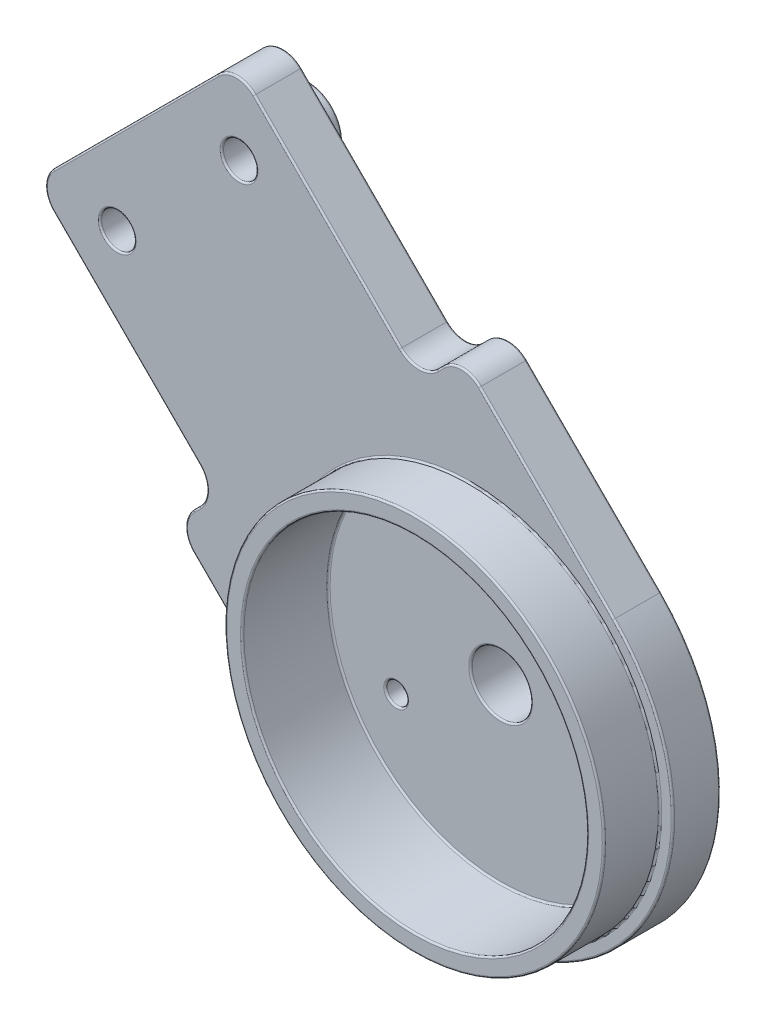
SolidWorks part; units mm, degrees
ref_plane "Front Plane" through (0, 0, 0) normal (0, 0, 1) x (1, 0, 0)
ref_plane "Top Plane" through (0, 0, 0) normal (0, 1, 0) x (1, 0, 0)
ref_plane "Right Plane" through (0, 0, 0) normal (1, 0, 0) x (0, 0, -1)
sketch "Sketch1" plane through (0, 0, 0) normal (0, 0, 1) x (1, 0, 0)
  line L0 (-100, 0) -> (100, 0) construction
  line L1 (-100, 0) -> (0, 100) construction
  line L2 (0, 100) -> (100, 0) construction
  line L3 (0, 0) -> (-50, 50) construction
  line L4 (-50, 50) -> (0, 0) construction
  line L5 (-40, 60) -> (40, 60) construction
  line L6 (0, 100) -> (0, 60) construction
  circle A0 centre (-100, 0) radius 20
  circle A1 centre (0, 0) radius 20
  circle A2 centre (100, 0) radius 20
  point P5 (0, 0)
  dimension "D5" = 40
  dimension "D1" = 200
  dimension "D2" = 90
  dimension "D3" = 90
  dimension "D4" = 80
sketch "Sketch2" plane through (0, 0, 0) normal (0, 0, 1) x (1, 0, 0)
  line L0 (-56.5165, 43.4835) -> (-40, 60) construction
  line L1 (-100, 0) -> (0, 100) construction
  line L2 (-40, 60) -> (40, 60) construction
  line L3 (40, 60) -> (86.565, 13.435) construction
  line L4 (0, 100) -> (100, 0) construction
  line L5 (-49.4454, 36.4124) -> (-35.8579, 50)
  line L6 (-35.8579, 50) -> (35.8579, 50)
  line L7 (35.8579, 50) -> (79.4939, 6.364)
  line L8 (-63.5876, 50.5546) -> (-44.1421, 70)
  line L9 (-44.1421, 70) -> (44.1421, 70)
  line L10 (44.1421, 70) -> (93.636, 20.5061)
  line L11 (-63.5876, 50.5546) -> (-49.4454, 36.4124)
  line L12 (93.636, 20.5061) -> (79.4939, 6.364)
  line L13 (81.9688, 8.8388) -> (95.4038, -4.5962)
  line L14 (91.1612, 18.0312) -> (104.5962, 4.5962)
  line L15 (75.9584, 9.8995) -> (90.1005, 24.0416) construction
  line L16 (0, 100) -> (0, 60) construction
  line L17 (-6, 70) -> (-3.4326, 85.5452)
  line L18 (6, 70) -> (3.4532, 85.4203)
  circle A0 centre (100, 0) radius 3.5
  circle A1 centre (100, 0) radius 10 construction
  arc A2 (95.4038, -4.5962) -> (104.5962, 4.5962) centre (100, 0) ccw
  circle A3 centre (100, 0) radius 0.5
  circle A4 centre (100, 0) radius 6.5 construction
  circle A5 centre (79.4939, 13.435) radius 1
  circle A6 centre (86.565, 20.5061) radius 1
  circle A7 centre (0, 60) radius 1.5
  circle A8 centre (0, 84.85) radius 1.5
  arc A9 (3.4532, 85.4203) -> (-3.4532, 85.4203) centre (0, 84.85) ccw
  circle A10 centre (0, 84.85) radius 3.5 construction
  circle A11 centre (-50, 50) radius 1.5
  dimension "D4" = 20
  dimension "D5" = 7
  dimension "D11" = 3
  dimension "D15" = 3
  dimension "D16" = 2
  dimension "D3" = 27.5
  dimension "D8" = 19
  dimension "D9" = 5
  dimension "D10" = 5
  dimension "5" = 5
  dimension "D12" = 14.85
  dimension "D7" = 6
  dimension "D14" = 6
  dimension "D1" = 10
  dimension "D2" = 10
  dimension "D6" = 3
  dimension "D13" = 2
sketch "Sketch3" plane through (0, 0, 0) normal (0, 0, 1) x (1, 0, 0)
  line L0 (-100, 0) -> (100, 0) construction
  line L1 (-86.6719, 13.3281) -> (-50, 50) construction
  line L2 (-24.0416, 9.8995) -> (-9.8995, 24.0416) construction
  line L3 (-50, 50) -> (-13.435, 13.435) construction
  line L4 (0, 0) -> (-50, 50) construction
  line L5 (-79.4939, 6.364) -> (-50, 35.8579)
  line L6 (-50, 35.8579) -> (-20.5061, 6.364)
  line L7 (-93.636, 20.5061) -> (-50, 64.1421)
  line L8 (-50, 64.1421) -> (-6.364, 20.5061)
  line L9 (-81.6799, 4.1779) -> (-50, 35.8579) construction
  line L10 (-95.8221, 18.3201) -> (-50, 64.1421) construction
  line L11 (-93.636, 20.5061) -> (-79.4939, 6.364)
  line L12 (-20.5061, 6.364) -> (-6.364, 20.5061)
  line L13 (-81.9688, 8.8388) -> (-95.4038, -4.5962)
  line L14 (-91.1612, 18.0312) -> (-104.5962, 4.5962)
  line L15 (-18.0312, 8.8388) -> (-4.5962, -4.5962)
  line L16 (-8.8388, 18.0312) -> (4.5962, 4.5962)
  line L17 (-88.751, 11.249) -> (-50, 50) construction
  line L18 (-90.1005, 24.0416) -> (-76.1469, 10.088) construction
  circle A0 centre (-100, 0) radius 10 construction
  circle A1 centre (-100, 0) radius 3.5
  circle A2 centre (0, 0) radius 10 construction
  circle A3 centre (0, 0) radius 3.5
  arc A4 (-4.5962, -4.5962) -> (4.5962, 4.5962) centre (0, 0) ccw
  arc A5 (-104.5962, 4.5962) -> (-95.4038, -4.5962) centre (-100, 0) ccw
  circle A6 centre (-86.565, 20.5061) radius 1
  circle A7 centre (0, 0) radius 6.5 construction
  circle A8 centre (-100, 0) radius 6.5 construction
  circle A9 centre (-79.4939, 13.435) radius 1
  circle A10 centre (-20.5061, 13.435) radius 1
  circle A11 centre (-13.435, 20.5061) radius 1
  circle A12 centre (-50, 50) radius 1.5 construction
  circle A13 centre (-50, 50) radius 1.5
  dimension "D1" = 20
  dimension "D2" = 7
  dimension "D9" = 2
  dimension "D7" = 19
  dimension "D8" = 19
  dimension "D10" = 5
  dimension "D11" = 5
  dimension "D12" = 5
  dimension "D13" = 5
  dimension "D14" = 5
  dimension "D15" = 5
  dimension "D3" = 3
  dimension "D4" = 3
  dimension "D5" = 10
  dimension "D6" = 10
sketch "Sketch4" plane through (0, 0, 0) normal (0, 0, 1) x (1, 0, 0)
  line L1 (57.5, 96.35) -> (57.5, 86.35)
  line L2 (57.5, 86.35) -> (44.1421, 70)
  line L3 (44.1421, 70) -> (-44.1421, 70)
  line L4 (-44.1421, 70) -> (-57.5, 86.35)
  line L5 (-57.5, 86.35) -> (-57.5, 96.35)
  line L7 (-57.5, 96.35) -> (57.5, 96.35)
  line L8 (-4, 60) -> (-4, 70)
  line L9 (4, 60) -> (4, 70)
  line L10 (-22.4799, 87.85) -> (22.5201, 87.85) construction
  line L11 (-22.4799, 92.35) -> (22.5201, 92.35)
  line L12 (-22.4799, 83.35) -> (22.5201, 83.35)
  circle A0 centre (0, 60) radius 1.5 construction
  circle A1 centre (0, 60) radius 1.5
  arc A2 (-4, 60) -> (4, 60) centre (0, 60) ccw
  circle A3 centre (0, 60) radius 4 construction
  arc A4 (-22.4799, 92.35) -> (-22.4799, 83.35) centre (-22.4799, 87.85) ccw
  arc A5 (22.5201, 83.35) -> (22.5201, 92.35) centre (22.5201, 87.85) ccw
  circle A6 centre (0, 84.85) radius 1.5 construction
  point P0 (0, 96.35)
  point P22 (0.0201, 87.85)
  dimension "D1" = 115
  dimension "D2" = 10
  dimension "D4" = 45
  dimension "D5" = 9
  dimension "D6" = 45
  dimension "D7" = 4
  dimension "D3" = 2.5
sketch "Sketch5" plane through (0, 0, 0) normal (0, 0, 1) x (1, 0, 0)
  line L0 (74.7209, 13.6118) -> (86.3882, 25.2791)
  line L1 (75.9584, 9.8995) -> (90.1005, 24.0416) construction
  line L2 (0, 100) -> (100, 0) construction
  line L3 (74.7209, 13.6118) -> (85.3275, 3.0052)
  line L4 (85.3275, 3.0052) -> (82.8527, 0.5303)
  line L5 (82.8527, 0.5303) -> (91.6915, -8.3085)
  line L6 (93.636, 20.5061) -> (79.4939, 6.364) construction
  line L7 (100, 0) -> (89.2055, 10.7945) construction
  line L8 (99.4697, 17.1473) -> (108.3085, 8.3085)
  line L9 (96.9948, 14.6725) -> (99.4697, 17.1473)
  line L10 (86.3882, 25.2791) -> (96.9948, 14.6725)
  circle A0 centre (100, 0) radius 10 construction
  circle A1 centre (100, 0) radius 10
  arc A2 (91.6915, -8.3085) -> (108.3085, 8.3085) centre (100, 0) ccw
  circle A3 centre (100, 0) radius 11.75 construction
  circle A4 centre (86.565, 20.5061) radius 1 construction
  circle A5 centre (86.565, 20.5061) radius 1
  circle A6 centre (79.4939, 13.435) radius 1 construction
  circle A7 centre (79.4939, 13.435) radius 1
  point P26 (52.6936, 17.3579)
  dimension "D2" = 16.5
  dimension "D4" = 12.5
  dimension "D5" = 15
  dimension "D1" = 1.75
extrude "Boss-Extrude1" add sketch "Sketch5" along normal blind 2.75
sketch "Sketch7" plane through (0, 0, 0) normal (0, 0, -1) x (-1, 0, 0)
  circle A0 centre (-100, 0) radius 10
extrude "Boss-Extrude2" add sketch "Sketch7" against normal blind 1
sketch "Sketch8" plane through (0, 0, 1) normal (0, 0, 1) x (1, 0, 0)
  circle A0 centre (100, 0) radius 11
  circle A1 centre (100, 0) radius 10
  circle A2 centre (100, 0) radius 10
  dimension "D1" = 0
  dimension "D2" = 1
extrude "Boss-Extrude3" add sketch "Sketch8" along normal blind 5
fillet "Fillet1" radius 1.5 6 edges at (74.7209, 13.6118, 1.375) (96.9948, 14.6725, 1.375) (99.4697, 17.1473, 1.375) (82.8527, 0.5303, 1.375) (85.3275, 3.0052, 1.375) (86.3882, 25.2791, 1.375)
sketch "Sketch9" plane through (0, 0, 0) normal (0, 0, -1) x (-1, 0, 0)
  circle A0 centre (-86.565, 20.5061) radius 1 construction
  circle A1 centre (-86.565, 20.5061) radius 1
  circle A2 centre (-79.4939, 13.435) radius 1 construction
  circle A3 centre (-79.4939, 13.435) radius 1
  circle A4 centre (-86.565, 20.5061) radius 2
  circle A5 centre (-79.4939, 13.435) radius 2
  dimension "D1" = 1
extrude "Boss-Extrude4" add sketch "Sketch9" along normal blind 1.25
sketch "Sketch10" plane through (0, 0, 0) normal (0, 0, -1) x (-1, 0, 0)
  circle A0 centre (-100, 0) radius 1.75
  dimension "D1" = 3.5
extrude "Cut-Extrude1" cut sketch "Sketch10" against normal through all both and the other way through all
sketch "Sketch12" plane through (0, 0, 0) normal (0, 0, -1) x (-1, 0, 0)
  circle A0 centre (-100, 0) radius 1.75
  circle A1 centre (-100, 0) radius 3.45
  dimension "D1" = 6.9
extrude "Boss-Extrude6" add sketch "Sketch12" along normal blind 4.25
sketch "Sketch14" plane through (0, 0, 0) normal (0, 0, -1) x (-1, 0, 0)
  line L0 (-100, 0) -> (-100, 7) construction
  circle A0 centre (-100, 7) radius 0.625
  circle A1 centre (-93.9378, -3.5) radius 0.625
  circle A2 centre (-106.0622, -3.5) radius 0.625
  point P11 (-100, 0)
  dimension "D1" = 1.25
  dimension "D2" = 7
  dimension "D3" = 3
extrude "Cut-Extrude2" cut sketch "Sketch14" against normal through all both and the other way through all
fillet "Fillet2" radius 0.1 50 edges at (105.4372, -3.5, 1) (106.6872, -3.5, 0) (93.3128, -3.5, 1) (94.5628, -3.5, 0) (99.375, 7, 1) (100.625, 7, 0) (98.25, 0, -4.25) (96.55, 0, -4.25) (98.25, 0, 1) (77.4939, 13.435, -1.25) (78.4939, 13.435, -1.25) (85.565, 20.5061, -1.25) (84.565, 20.5061, -1.25) (110, 0, 6) (111, 0, 6) (111, 0, 2.75) (90, 0, 1) (80.4939, 13.435, 2.75) (87.565, 20.5061, 2.75) (80.0242, 8.3085, 2.75) (80.0242, 8.3085, 0) (84.0901, 1.7678, 0) (84.0901, 1.7678, 2.75) (87.8024, -4.4194, 2.75) (87.8024, -4.4194, 0) (108.3085, -8.3085, 0) (108.3085, -8.3085, 2.75) (104.4194, 12.1976, 0) (104.4194, 12.1976, 2.75) (98.2322, 15.9099, 0) (98.2322, 15.9099, 2.75) (80.5546, 19.4454, 0) (80.5546, 19.4454, 2.75) (91.6915, 19.9758, 2.75) (86.3882, 24.6577, 2.75) (86.3882, 24.6577, 0) (83.474, 0.5303, 2.75) (83.474, 0.5303, 0) (99.4697, 16.526, 2.75) (99.4697, 16.526, 0) (75.3423, 13.6118, 2.75) (75.3423, 13.6118, 0) (96.9948, 15.2938, 2.75) (96.9948, 15.2938, 0) (84.7062, 3.0052, 2.75) (84.7062, 3.0052, 0) (88.565, 20.5061, 0) (81.4939, 13.435, 0) (103.45, 0, 0) (91.6915, 19.9758, 0)
